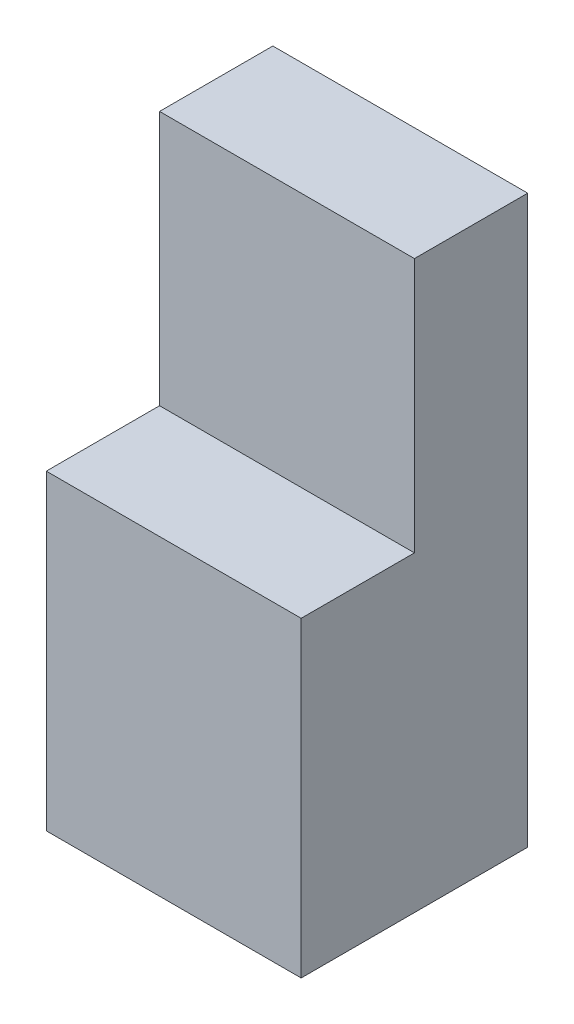
SolidWorks part; units mm, degrees
ref_plane "Front Plane" through (0, 0, 0) normal (0, 0, 1) x (1, 0, 0)
ref_plane "Top Plane" through (0, 0, 0) normal (0, 1, 0) x (1, 0, 0)
ref_plane "Right Plane" through (0, 0, 0) normal (1, 0, 0) x (0, 0, -1)
sketch "Sketch1" plane through (0, 0, 0) normal (0, 0, 1) x (1, 0, 0)
  line L1 (-9, 20) -> (9, 20)
  line L2 (-9, 20) -> (-9, -20)
  line L3 (-9, -20) -> (9, -20)
  line L4 (9, 20) -> (9, -20)
  point P4 (-9, 0)
  point P6 (0, 20)
  dimension "D1" = 18
  dimension "D2" = 40
extrude "Boss-Extrude1" add sketch "Sketch1" along normal blind 8
sketch "Sketch2" plane through (0, 0, 8) normal (0, 0, 1) x (1, 0, 0)
  line L0 (9, -20) -> (9, 20) construction
  line L1 (-9, -20) -> (9, -20)
  line L2 (-9, -20) -> (-9, 2)
  line L3 (-9, 2) -> (9, 2)
  line L4 (9, -20) -> (9, 2)
  dimension "D1" = 22
extrude "Boss-Extrude2" add sketch "Sketch2" along normal blind 8
